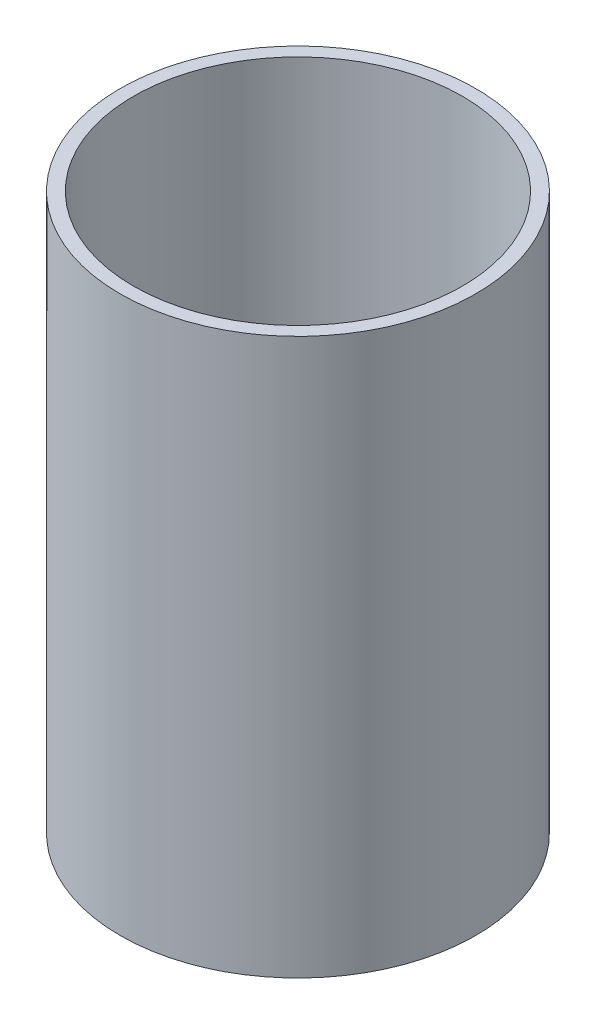
SolidWorks part; units mm, degrees
ref_plane "Front Plane" through (0, 0, 0) normal (0, 0, 1) x (1, 0, 0)
ref_plane "Top Plane" through (0, 0, 0) normal (0, 1, 0) x (1, 0, 0)
ref_plane "Right Plane" through (0, 0, 0) normal (1, 0, 0) x (0, 0, -1)
sketch "Sketch1" plane through (0, 0, 0) normal (0, 1, 0) x (1, 0, 0)
  circle A0 centre (0, 0) radius 16
  circle A1 centre (0, 0) radius 14.8
  dimension "D1" = 1.2
  dimension "D2" = 32
extrude "Boss-Extrude1" add sketch "Sketch1" along normal blind 50
sketch "Sketch2" plane through (0, 0, 0) normal (1, 0, 0) x (0, 0, -1)
  line L0 (0, 0) -> (0, 50) construction
  line L1 (16, 50) -> (-16, 50) construction
  circle A0 centre (0, 25) radius 0.5
  point P8 (0, 25)
  dimension "D1" = 1
extrude "Cut-Extrude1" cut sketch "Sketch2" against normal through all
